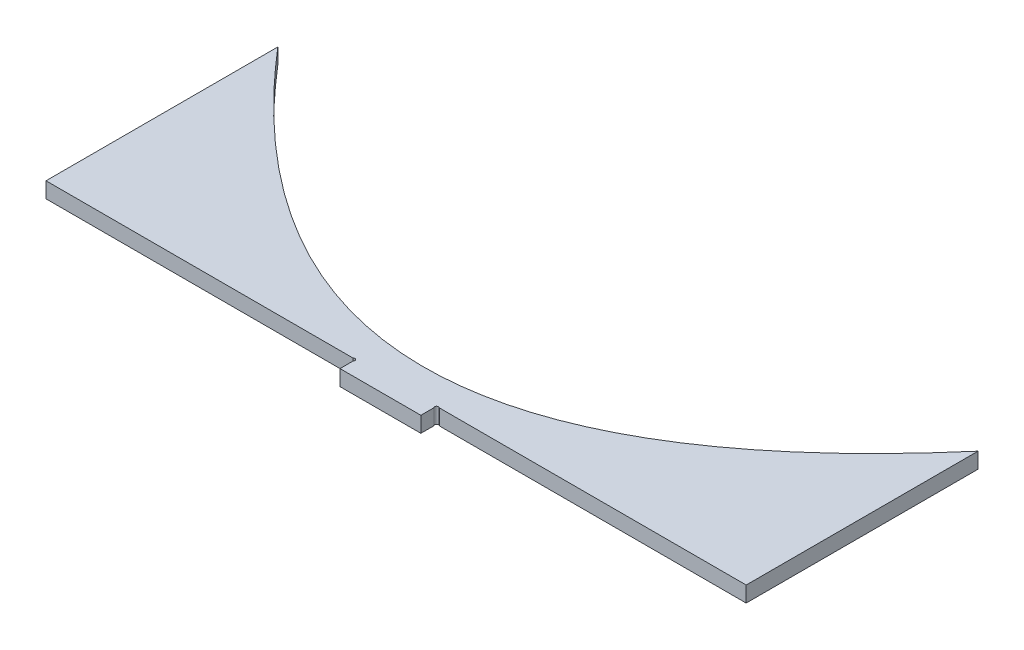
SolidWorks part; units mm, degrees
ref_plane "Alzado" through (0, 0, 0) normal (0, 0, 1) x (1, 0, 0)
ref_plane "Planta" through (0, 0, 0) normal (0, 1, 0) x (1, 0, 0)
ref_plane "Vista lateral" through (0, 0, 0) normal (1, 0, 0) x (0, 0, -1)
sketch "Croquis1" plane through (0, 0, 0) normal (0, 1, 0) x (1, 0, 0)
  line L0 (-237.4382, 168.6502) -> (-237.4382, -9.1064)
  line L1 (-237.4382, -9.1064) -> (-2.1213, -9.1064)
  line L2 (299.4382, -9.1064) -> (299.4382, 168.6502)
  line L3 (31, 19.7658) -> (31, -17.721) construction
  line L4 (31, -21.1064) -> (0, -21.1064)
  line L5 (0, -11.2277) -> (0, -21.1064)
  line L6 (31, -21.1064) -> (62, -21.1064)
  line L7 (62, -21.1064) -> (62, -11.2277)
  line L9 (64.1213, -9.1064) -> (299.4382, -9.1064)
  arc A0 (0, -11.2277) -> (-2.1213, -9.1064) centre (-1.0607, -10.167) ccw
  arc A1 (64.1213, -9.1064) -> (62, -11.2277) centre (63.0607, -10.167) ccw
  parabola Q0 (31, 12) -> (-237.4382, 168.6502) focus (31, 127) apex (31, 12)
  parabola Q1 (299.4382, 168.6502) -> (31, 12) focus (31, 127) apex (31, 12)
  dimension "D1" = 177.7565
  dimension "D2" = 536.8764
  dimension "D3" = 62
extrude "Saliente-Extruir1" add sketch "Croquis1" along normal blind 12
